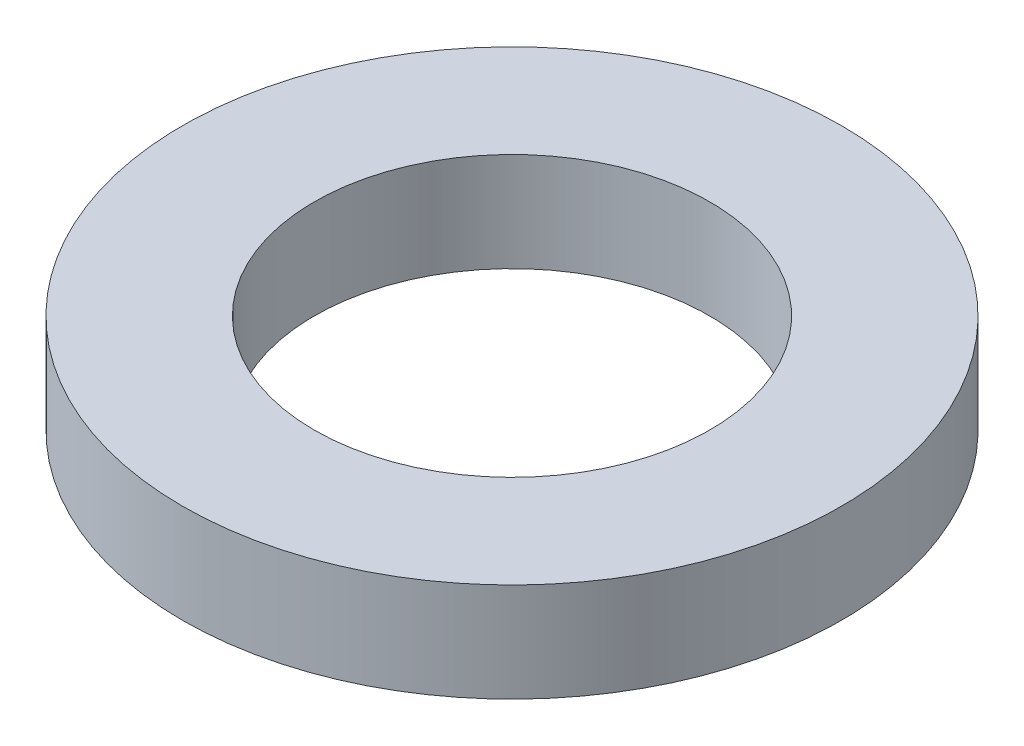
SolidWorks part; units mm, degrees
ref_plane "Front Plane" through (0, 0, 0) normal (0, 0, 1) x (1, 0, 0)
ref_plane "Top Plane" through (0, 0, 0) normal (0, 1, 0) x (1, 0, 0)
ref_plane "Right Plane" through (0, 0, 0) normal (1, 0, 0) x (0, 0, -1)
sketch "Sketch1" plane through (0, 0, 0) normal (0, 1, 0) x (1, 0, 0)
  circle A0 centre (0, 0) radius 6
  circle A1 centre (0, 0) radius 10
  dimension "D1" = 20
  dimension "D2" = 12
extrude "Boss-Extrude1" add sketch "Sketch1" along normal blind 3
